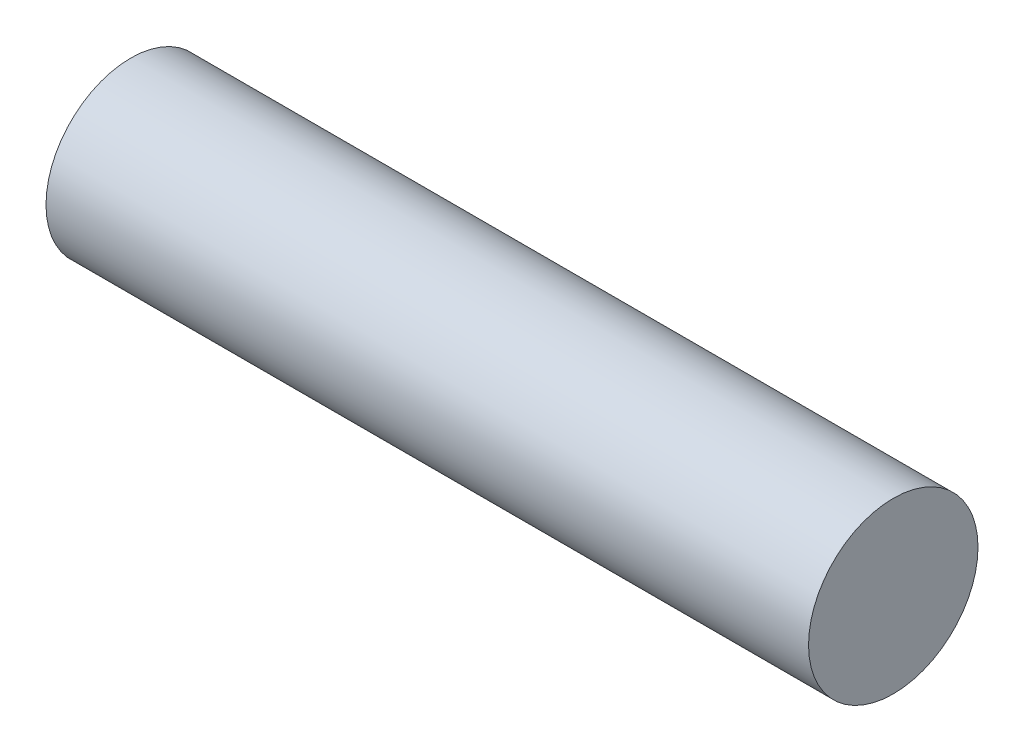
SolidWorks part; units mm, degrees
ref_plane "Front" through (0, 0, 0) normal (0, 0, 1) x (1, 0, 0)
ref_plane "Top" through (0, 0, 0) normal (0, 1, 0) x (1, 0, 0)
ref_plane "Right" through (0, 0, 0) normal (1, 0, 0) x (0, 0, -1)
sketch "Sketch1" plane through (0, 0, 0) normal (1, 0, 0) x (0, 0, -1)
  circle A0 centre (0, 0) radius 6.35
  dimension "D1" = 12.7
extrude "Boss-Extrude1" add sketch "Sketch1" along normal mid plane 57.15
